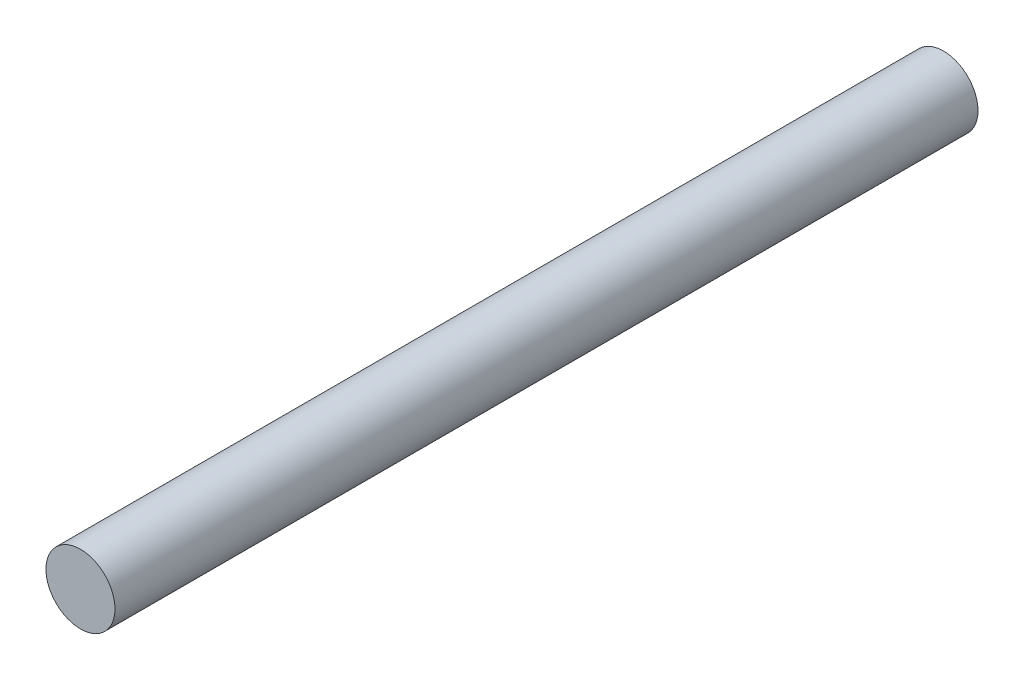
SolidWorks part; units mm, degrees
material "Nickel"
ref_plane "Front Plane" through (0, 0, 0) normal (0, 0, 1) x (1, 0, 0)
ref_plane "Top Plane" through (0, 0, 0) normal (0, 1, 0) x (1, 0, 0)
ref_plane "Right Plane" through (0, 0, 0) normal (1, 0, 0) x (0, 0, -1)
sketch "Sketch1" plane through (0, 0, 0) normal (0, 0, 1) x (1, 0, 0)
  circle A0 centre (-5.9871, 4.9645) radius 4
  dimension "D1" = 8
extrude "Boss-Extrude1" add sketch "Sketch1" along normal blind 100
